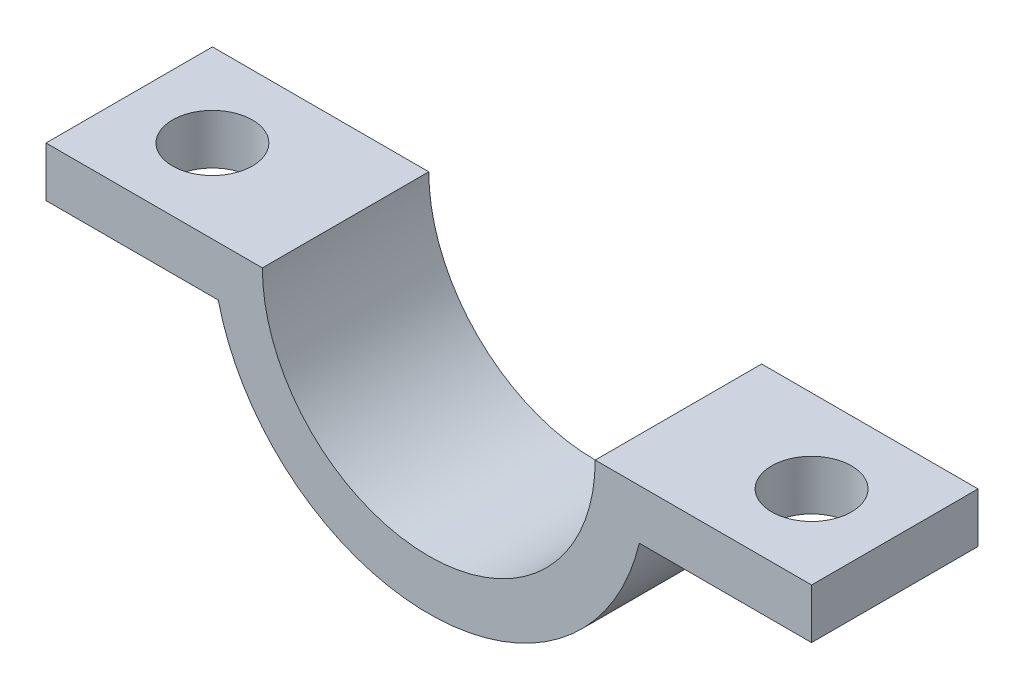
SolidWorks part; units mm, degrees
material "Windform GT"
ref_plane "Front Plane" through (0, 0, 0) normal (0, 0, 1) x (1, 0, 0)
ref_plane "Top Plane" through (0, 0, 0) normal (0, 1, 0) x (1, 0, 0)
ref_plane "Right Plane" through (0, 0, 0) normal (1, 0, 0) x (0, 0, -1)
sketch "Sketch1" plane through (0, 0, 0) normal (0, 0, 1) x (1, 0, 0)
  line L0 (0, 0) -> (0, -8.856) construction
  line L1 (5, 0) -> (11.5, 0)
  line L2 (11.5, 0) -> (11.5, -1.5)
  line L3 (11.5, -1.5) -> (6.3246, -1.5)
  line L4 (-11.5, -1.5) -> (-6.3246, -1.5)
  line L5 (-11.5, 0) -> (-11.5, -1.5)
  line L6 (-5, 0) -> (-11.5, 0)
  arc A0 (-6.3246, -1.5) -> (6.3246, -1.5) centre (0, 0) ccw
  arc A1 (-5, 0) -> (5, 0) centre (0, 0) ccw
  dimension "D1" = 5
  dimension "D2" = 6.5
  dimension "D3" = 1.5
  dimension "D4" = 11.5
extrude "Boss-Extrude1" add sketch "Sketch1" along normal mid plane 5
sketch "Sketch2" plane through (0, 0, 0) normal (0, 1, 0) x (1, 0, 0)
  line L0 (0, 0) -> (-11.5, 0) construction
  line L1 (-11.5, -2.5) -> (-11.5, 2.5) construction
  line L2 (0, 0) -> (0, 6.0321) construction
  circle A0 centre (-9, 0) radius 1.2
  circle A1 centre (9, 0) radius 1.2
  dimension "D1" = 2.4
  dimension "D2" = 2.5
extrude "Cut-Extrude1" cut sketch "Sketch2" against normal through all
